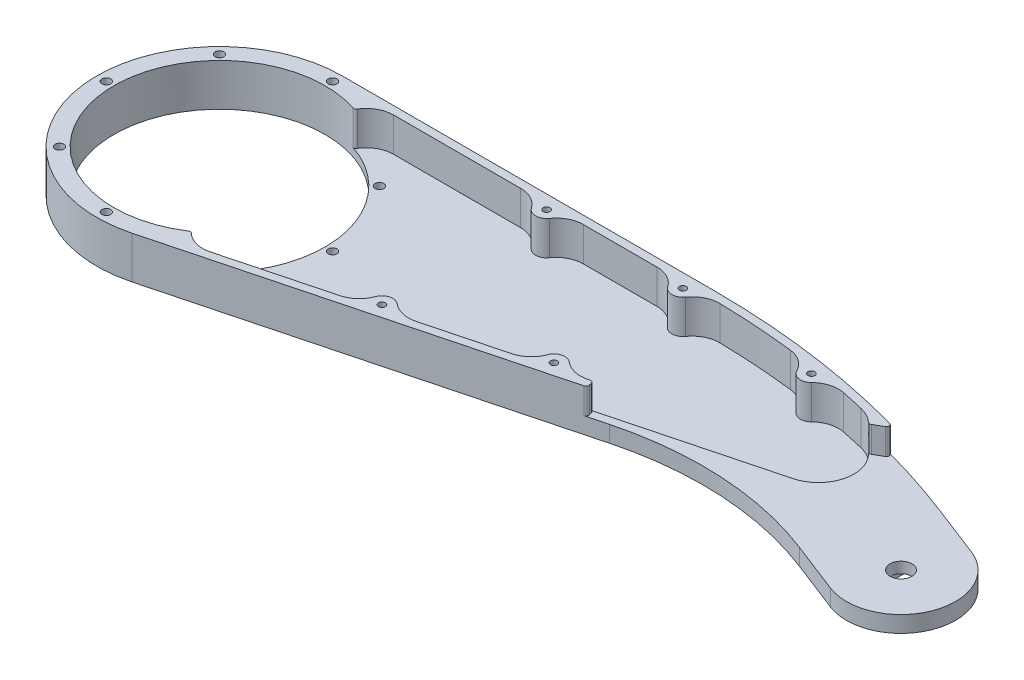
SolidWorks part; units mm, degrees
ref_plane "Спереди" through (0, 0, 0) normal (0, 0, 1) x (1, 0, 0)
ref_plane "Сверху" through (0, 0, 0) normal (0, 1, 0) x (1, 0, 0)
ref_plane "Справа" through (0, 0, 0) normal (1, 0, 0) x (0, 0, -1)
ref_plane "Плоскость4" through (0, 0, 0) normal (0, -1, 0) x (1, 0, 0)
sketch "Эскиз1" plane through (0, 0, 0) normal (0, -1, 0) x (1, 0, 0)
  line L0 (31.7794, 35.0947) -> (32.5393, 37.9968)
  line L1 (32.5393, 37.9968) -> (11.3988, 43.5324)
  line L2 (0, -45) -> (136.6047, -45)
  line L3 (211.069, -33.2121) -> (207.1483, -30.9537)
  line L4 (118.5109, -42) -> (21.8532, -42)
  arc A0 (11.3988, 43.5324) -> (0, -45) centre (0, 0) ccw
  arc A1 (136.6047, -45) -> (210.8334, -35.0433) centre (136.6047, 236.6697) ccw
  arc A2 (210.8334, -35.0433) -> (211.069, -33.2121) centre (210.5698, -34.0786) ccw
  arc A3 (207.1483, -30.9537) -> (200.8795, -34.4863) centre (197.8811, -21.8368) cw
  arc A4 (200.8795, -34.4863) -> (141.6391, -41.9545) centre (136.6047, 236.6697) cw
  arc A5 (141.6391, -41.9545) -> (133.2738, -37.7018) centre (141.4585, -31.9562) cw
  arc A6 (133.2738, -37.7018) -> (126.7174, -37.7143) centre (130, -40) ccw
  arc A7 (126.7174, -37.7143) -> (118.5109, -42) centre (118.5109, -32) cw
  arc A8 (21.8532, -42) -> (12.9365, -36.5268) centre (21.8532, -32) cw
  arc A9 (12.9365, -36.5268) -> (21.7671, 32.0587) centre (0, 0) ccw
  arc A10 (21.7671, 32.0587) -> (31.7794, 35.0947) centre (29.2463, 25.4208) cw
extrude "Бобышка-Вытянуть1" add sketch "Эскиз1" against normal blind 9.5
sketch "Эскиз2" plane through (21.1405, 0, -5.5356) normal (0.9674, 0, -0.2533) x (-0.2533, 0, -0.9674)
  line L0 (-42, 0) -> (-45, 0)
  line L1 (-45, 0) -> (-45, 9.5)
  line L2 (-45, 9.5) -> (-42, 9.5)
  line L3 (-42, 9.5) -> (-42, 0)
extrude "Бобышка-Вытянуть2" add sketch "Эскиз2" along normal blind 115.0557
sketch "Эскиз3" plane through (0, 9.5, 0) normal (0, 1, 0) x (-1, 0, 0)
  line L0 (0, -45) -> (-136.6047, -45)
  line L1 (-238.5994, -25.8849) -> (-257.2421, -18.6427)
  line L2 (-242.7579, 18.6427) -> (-187.8755, -2.6774)
  line L3 (-187.8755, -2.6774) -> (-11.3988, 43.5324)
  arc A0 (-11.3988, 43.5324) -> (0, -45) centre (0, 0) cw
  arc A1 (-136.6047, -45) -> (-238.5994, -25.8849) centre (-136.6047, 236.6697) cw
  arc A2 (-257.2421, -18.6427) -> (-242.7579, 18.6427) centre (-250, 0) cw
extrude "Бобышка-Вытянуть3" add sketch "Эскиз3" along normal blind 6
sketch "Эскиз4" plane through (0, 9.5, 0) normal (0, -1, 0) x (1, 0, 0)
  line L0 (201.1741, -9.2608) -> (31.7794, 35.0947)
  line L1 (21.8532, -42) -> (118.5109, -42)
  arc A0 (31.7794, 35.0947) -> (21.7671, 32.0587) centre (29.2463, 25.4208) ccw
  arc A1 (21.7671, 32.0587) -> (12.9365, -36.5268) centre (0, 0) cw
  arc A2 (12.9365, -36.5268) -> (21.8532, -42) centre (21.8532, -32) ccw
  arc A3 (118.5109, -42) -> (126.7174, -37.7143) centre (118.5109, -32) ccw
  arc A4 (126.7174, -37.7143) -> (133.2738, -37.7018) centre (130, -40) cw
  arc A5 (133.2738, -37.7018) -> (141.6391, -41.9545) centre (141.4585, -31.9562) ccw
  arc A6 (141.6391, -41.9545) -> (200.8795, -34.4863) centre (136.6047, 236.6697) ccw
  arc A7 (200.8795, -34.4863) -> (201.1741, -9.2608) centre (197.8811, -21.8368) ccw
extrude "Вырез-Вытянуть1" cut sketch "Эскиз4" against normal blind 3
sketch "Эскиз5" plane through (0, 12.5, 0) normal (0, -1, 0) x (1, 0, 0)
  line L0 (69.3922, 25.2459) -> (91.621, 19.4253)
  arc A0 (76.2455, 19.0212) -> (69.3922, 25.2459) centre (66.8591, 15.572) ccw
  arc A1 (91.621, 19.4253) -> (82.5966, 17.3581) centre (89.088, 9.7515) ccw
  arc A2 (82.5966, 17.3581) -> (76.2455, 19.0212) centre (80, 20.4008) cw
extrude "Бобышка-Вытянуть4" add sketch "Эскиз5" along normal blind 12.5
sketch "Эскиз6" plane through (0, 12.5, 0) normal (0, -1, 0) x (1, 0, 0)
  line L0 (119.3922, 12.1535) -> (141.621, 6.333)
  arc A0 (126.2455, 5.9288) -> (119.3922, 12.1535) centre (116.8591, 2.4797) ccw
  arc A1 (141.621, 6.333) -> (132.5966, 4.2658) centre (139.088, -3.3409) ccw
  arc A2 (132.5966, 4.2658) -> (126.2455, 5.9288) centre (130, 7.3085) cw
extrude "Бобышка-Вытянуть5" add sketch "Эскиз6" along normal blind 12.5
sketch "Эскиз7" plane through (0, 12.5, 0) normal (0, -1, 0) x (1, 0, 0)
  arc A0 (169.3505, -40.0694) -> (177.0946, -34.6607) centre (168.1755, -30.1387) ccw
  arc A1 (177.0946, -34.6607) -> (183.4802, -33.6307) centre (180.6622, -36.4696) cw
  arc A2 (183.4802, -33.6307) -> (192.5321, -36.3302) centre (190.5252, -26.5336) ccw
  arc A3 (192.5321, -36.3302) -> (169.3505, -40.0694) centre (136.6047, 236.6697) cw
extrude "Бобышка-Вытянуть6" add sketch "Эскиз7" along normal blind 12.5
sketch "Эскиз8" plane through (0, 12.5, 0) normal (0, -1, 0) x (1, 0, 0)
  line L0 (91.4891, -42) -> (68.5109, -42)
  arc A0 (83.2826, -37.7143) -> (91.4891, -42) centre (91.4891, -32) ccw
  arc A1 (68.5109, -42) -> (76.7174, -37.7143) centre (68.5109, -32) ccw
  arc A2 (76.7174, -37.7143) -> (83.2826, -37.7143) centre (80, -40) cw
extrude "Бобышка-Вытянуть7" add sketch "Эскиз8" along normal blind 12.5
sketch "Эскиз9" plane through (0, 15.5, 0) normal (0, 1, 0) x (-1, 0, 0)
  line L0 (-245.75, -6.7777) -> (-245.75, 6.7777)
  line L1 (-254.25, 6.7777) -> (-254.25, -6.7777)
  arc A0 (-254.25, -6.7777) -> (-245.75, -6.7777) centre (-250, 0) ccw
  arc A1 (-245.75, 6.7777) -> (-254.25, 6.7777) centre (-250, 0) ccw
extrude "Вырез-Вытянуть2" cut sketch "Эскиз9" against normal blind 2
ref_plane "Плоскость5" through (0, 0, 0) normal (0, 0, -1) x (-1, 0, 0)
sketch "Эскиз10" plane through (0, 0, 0) normal (0, 0, -1) x (-1, 0, 0)
  line L0 (-38.75, 0) -> (0, 0)
  line L1 (0, 0) -> (0, 15.5)
  line L2 (0, 15.5) -> (-38.75, 15.5)
  line L3 (-38.75, 15.5) -> (-38.75, 0)
  line L4 (0, 0) -> (0, 15.5) construction
revolve "Вырез-Повернуть1" cut sketch "Эскиз10" angle 360 about L4
hole_wizard "Диаметр отверстия Ø8.0 (8)1" positions "Эскиз12" profile "Эскиз11" hole size "Ø8.0" standard "Ansi Metric"
sketch "Эскиз12" plane through (0, 9.5, 0) normal (0, -1, 0) x (-1, 0, 0)
  point P0 (-250, 0)
sketch "Эскиз11" plane through (250, 9.5, 0) normal (1, 0, 0) x (0, 0, -1)
  line L0 (0, 0) -> (0, 6)
  line L1 (0, 6) -> (4, 6)
  line L2 (4, 6) -> (4, 0)
  line L5 (4, 0) -> (0, 0)
  line L11 (0, -6.35) -> (0, 107.95) construction
  dimension "Диаметр сквозного отверстия" = 8
  dimension "Глубина сквозного отверстия" = 6
hole_wizard "Диаметр отверстия Ø2.5 (2.5)1" positions "Эскиз14" profile "Эскиз13" hole size "Ø2.5" standard "Ansi Metric"
sketch "Эскиз14" plane through (0, 15.5, 0) normal (0, 1, 0) x (1, 0, 0)
  point P0 (130, -7.3085)
  point P1 (130, 40)
  point P2 (80, -20.4008)
  point P3 (180.6622, 36.4696)
  point P4 (80, 40)
sketch "Эскиз13" plane through (130, 15.5, 7.3085) normal (1, 0, 0) x (0, 0, 1)
  line L0 (0, 0) -> (0, 15.5)
  line L1 (0, 15.5) -> (1.25, 15.5)
  line L2 (1.25, 15.5) -> (1.25, 0)
  line L5 (1.25, 0) -> (0, 0)
  line L11 (0, -6.35) -> (0, 107.95) construction
  dimension "Диаметр сквозного отверстия" = 2.5
  dimension "Глубина сквозного отверстия" = 15.5
hole_wizard "Диаметр отверстия Ø3.2 (3.2)1" positions "Эскиз16" profile "Эскиз15" hole size "Ø3.2" standard "Ansi Metric"
sketch "Эскиз16" plane through (0, 15.5, 0) normal (0, 1, 0) x (1, 0, 0)
  point P0 (29.3449, 29.3449)
  point P1 (41.5, 0)
  point P2 (29.3449, -29.3449)
sketch "Эскиз15" plane through (29.3449, 15.5, -29.3449) normal (1, 0, 0) x (0, 0, 1)
  line L0 (0, 0) -> (0, 15.5)
  line L1 (0, 15.5) -> (1.6, 15.5)
  line L2 (1.6, 15.5) -> (1.6, 0)
  line L5 (1.6, 0) -> (0, 0)
  line L11 (0, -6.35) -> (0, 107.95) construction
  dimension "Диаметр сквозного отверстия" = 3.2
  dimension "Глубина сквозного отверстия" = 15.5
hole_wizard "Диаметр отверстия Ø3.2 (3.2)2" positions "Эскиз18" profile "Эскиз17" hole size "Ø3.2" standard "Ansi Metric"
sketch "Эскиз18" plane through (0, 15.5, 0) normal (0, 1, 0) x (1, 0, 0)
  point P0 (-29.3449, 29.3449)
  point P1 (0, 41.5)
  point P2 (0, -41.5)
  point P3 (-29.3449, -29.3449)
  point P4 (-41.5, 0)
sketch "Эскиз17" plane through (-29.3449, 15.5, -29.3449) normal (1, 0, 0) x (0, 0, 1)
  line L0 (0, 0) -> (0, 15.5)
  line L1 (0, 15.5) -> (1.6, 15.5)
  line L2 (1.6, 15.5) -> (1.6, 0)
  line L5 (1.6, 0) -> (0, 0)
  line L11 (0, -6.35) -> (0, 107.95) construction
  dimension "Диаметр сквозного отверстия" = 3.2
  dimension "Глубина сквозного отверстия" = 15.5
fillet "Скругление1" radius 1 5 edges at (143.0826, 4.75, 5.9503) (12.9365, 6.25, -36.5268) (21.7671, 6.25, 32.0587) (207.1483, 4.75, -30.9537) (143.8426, 4.75, 8.8524)
fillet "Скругление2" radius 2 4 edges at (254.25, 14.5, -6.7777) (254.25, 14.5, 6.7777) (245.75, 14.5, 6.7777) (245.75, 14.5, -6.7777)
fillet "Скругление3" radius 120 1 edges at (187.8755, 12.5, -2.6774)
mirror "Зеркальное отражение1" about plane through (0, 15.5, 0) normal (0, -1, 0) of bodies 116
delete or keep bodies "Тело-Удалить/Сохранить 1" type delete bodies bodies 116
